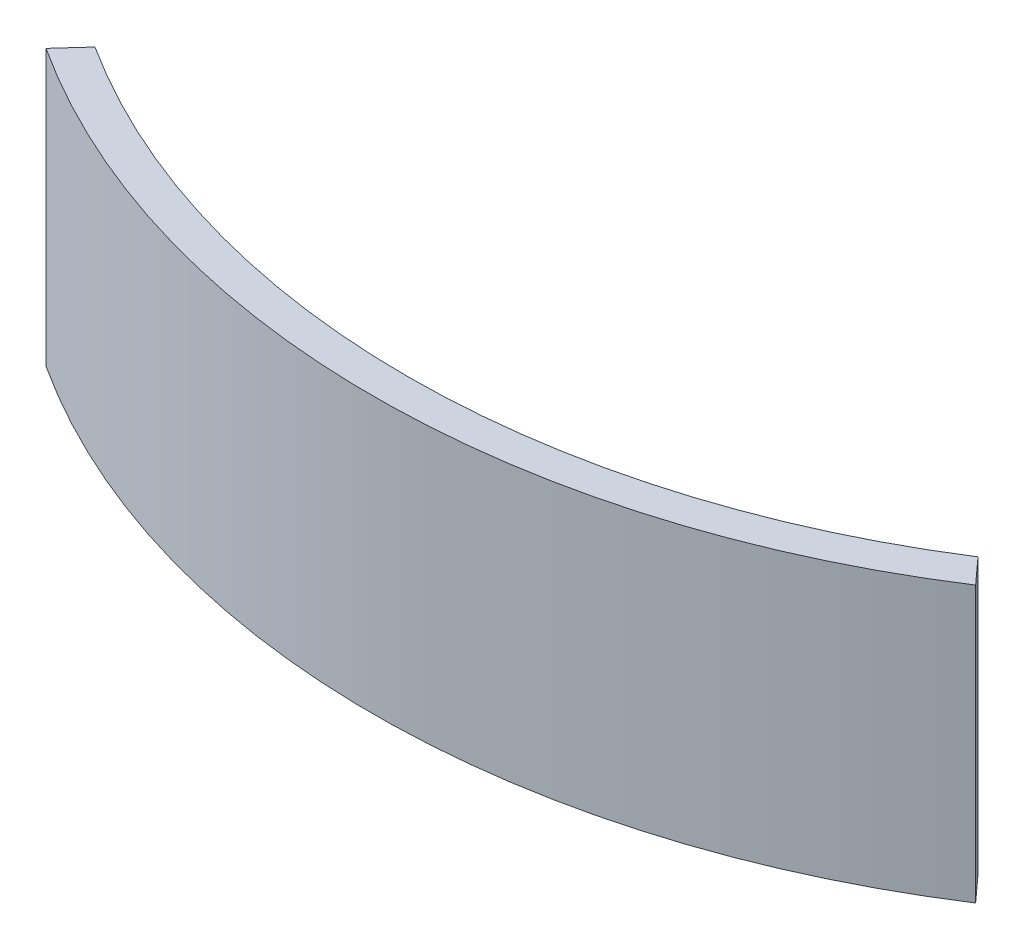
SolidWorks part; units mm, degrees
ref_plane "Front" through (0, 0, 0) normal (0, 0, 1) x (1, 0, 0)
ref_plane "Top" through (0, 0, 0) normal (0, 1, 0) x (1, 0, 0)
ref_plane "Right" through (0, 0, 0) normal (1, 0, 0) x (0, 0, -1)
sketch "Sketch1" plane through (0, 0, 0) normal (0, 1, 0) x (1, 0, 0)
  line L2 (0, 0) -> (0, -125) construction
  line L3 (-68.0341, -104.8635) -> (-64.63, -101.1087)
  line L4 (68.0341, -104.8635) -> (64.63, -101.1087)
  arc A0 (-68.0341, -104.8635) -> (68.0341, -104.8635) centre (0, 0) ccw
  arc A1 (-64.63, -101.1087) -> (64.63, -101.1087) centre (0, 0) ccw
  arc A2 (-65.3128, -100.669) -> (65.3128, -100.669) centre (0, 0) ccw construction
  dimension "D1" = 250
  dimension "D4" = 5
extrude "Boss-Extrude1" add sketch "Sketch1" along normal blind 40.3
